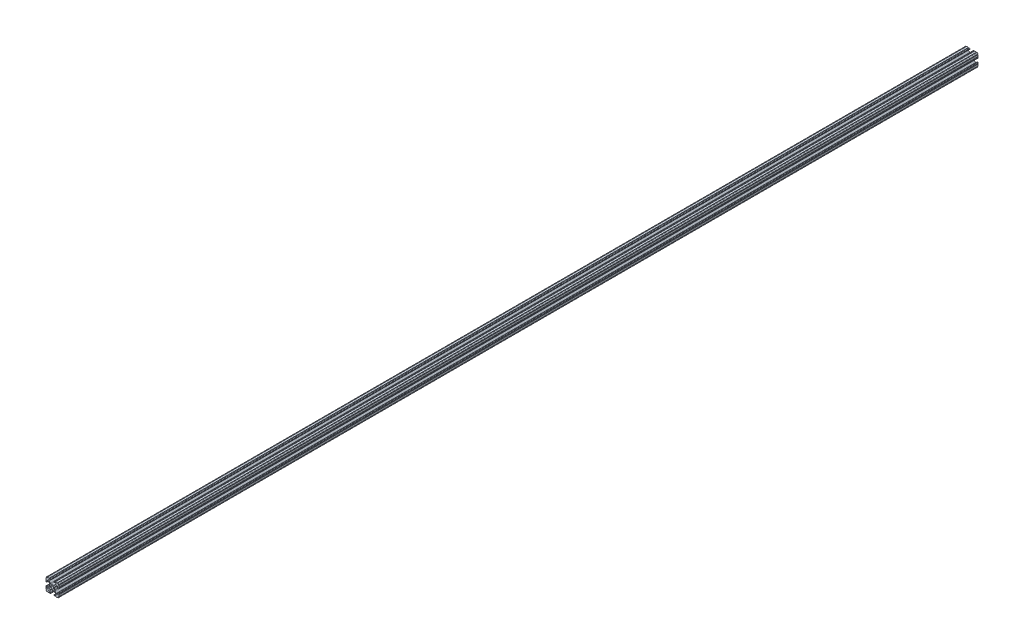
SolidWorks part; units mm, degrees
ref_plane "Front Plane" through (0, 0, 0) normal (0, 0, 1) x (1, 0, 0)
ref_plane "Top Plane" through (0, 0, 0) normal (0, 1, 0) x (1, 0, 0)
ref_plane "Right Plane" through (0, 0, 0) normal (1, 0, 0) x (0, 0, -1)
sketch "Sketch2" plane through (0, 0, 0) normal (0, 0, 1) x (1, 0, 0)
  line L0 (0, 12.7) -> (0, -12.7) construction
  line L1 (-12.7, 0) -> (12.7, 0) construction
  line L2 (3.2512, -12.7) -> (12.7, -12.7)
  line L3 (12.7, -12.7) -> (12.7, -3.2512)
  line L4 (3.2512, -12.7) -> (3.2512, -10.4902)
  line L5 (3.2512, -10.4902) -> (8.9276, -10.4902)
  line L6 (8.9276, -10.4902) -> (3.0856, -4.6482)
  line L7 (0, 0) -> (12.7, -12.7) construction
  line L8 (12.7, -3.2512) -> (10.4902, -3.2512)
  line L9 (10.4902, -3.2512) -> (10.4902, -8.9276)
  line L10 (10.4902, -8.9276) -> (4.6482, -3.0856)
  circle A0 centre (0, 0) radius 2.6035
  arc A1 (6.3485, -10.4902) -> (7.1039, -8.6665) centre (6.3485, -9.4219) ccw construction
  point P8 (0, -4.6482)
  dimension "Center Hole Diameter" = 5.207
  dimension "Rail Height" = 25.4
  dimension "Rail Width" = 25.4
  dimension "T-Slot Width" = 6.5024
  dimension "Slot Inner Width" = 14.8336
  dimension "Thickness" = 2.2098
  dimension "Slot Depth" = 5.842
  dimension "D1" = 2.2098
sketch "Sketch3" plane through (0, 0, 0) normal (1, 0, 0) x (0, 0, -1)
  line L0 (-914.4, -12.7) -> (914.4, -12.7) construction
  line L1 (-889, 0) -> (889, 0) construction
  dimension "Length" = 1828.8
  dimension "D1" = 25.4
sketch "Sketch4" plane through (0, 0, 0) normal (0, 0, 1) x (1, 0, 0)
  line L0 (4.1904, -12.7) -> (10.1173, -12.7)
  line L1 (3.2512, -12.7) -> (12.7, -12.7) construction
  line L2 (3.2512, -12.7) -> (3.2512, -10.4902) construction
  line L3 (3.2512, -10.4902) -> (8.9276, -10.4902) construction
  line L4 (3.2512, -11.4294) -> (3.2512, -11.7608)
  line L5 (4.1904, -10.4902) -> (6.3485, -10.4902)
  line L6 (0, -4.6482) -> (2.164, -4.6482)
  line L7 (8.9276, -10.4902) -> (3.0856, -4.6482) construction
  line L8 (3.7373, -5.2999) -> (7.1039, -8.6665)
  line L9 (12.7, -12.7) -> (12.7, -3.2512) construction
  line L10 (10.4902, -8.9276) -> (4.6482, -3.0856) construction
  line L11 (10.4902, -3.2512) -> (10.4902, -8.9276) construction
  line L12 (10.4902, -6.3485) -> (10.4902, -4.1904)
  line L13 (12.7, -3.2512) -> (10.4902, -3.2512) construction
  line L14 (11.4294, -3.2512) -> (11.7608, -3.2512)
  line L15 (12.7, -4.1904) -> (12.7, -10.1173)
  line L16 (8.6665, -7.1039) -> (5.2999, -3.7373)
  line L17 (4.6482, 0) -> (4.6482, -2.164)
  line L18 (-12.7, 0) -> (12.7, 0) construction
  line L19 (0, -4.6482) -> (0, -2.6035)
  line L20 (0, 12.7) -> (0, -12.7) construction
  line L21 (4.6482, 0) -> (2.6035, 0)
  arc A0 (3.2512, -11.7608) -> (4.1904, -12.7) centre (4.1904, -11.7608) ccw
  arc A2 (3.2512, -11.4294) -> (4.1904, -10.4902) centre (4.1904, -11.4294) cw
  arc A3 (6.3485, -10.4902) -> (7.1039, -8.6665) centre (6.3485, -9.4219) ccw
  arc A4 (2.164, -4.6482) -> (3.7373, -5.2999) centre (2.164, -6.8732) cw
  arc A5 (10.1173, -12.7) -> (12.7, -10.1173) centre (10.1173, -10.1173) ccw
  arc A6 (8.6665, -7.1039) -> (10.4902, -6.3485) centre (9.4219, -6.3485) ccw
  arc A7 (10.4902, -4.1904) -> (11.4294, -3.2512) centre (11.4294, -4.1904) cw
  arc A8 (11.7608, -3.2512) -> (12.7, -4.1904) centre (11.7608, -4.1904) cw
  arc A9 (5.2999, -3.7373) -> (4.6482, -2.164) centre (6.8732, -2.164) cw
  circle A10 centre (0, 0) radius 2.6035 construction
  arc A11 (0, -2.6035) -> (2.6035, 0) centre (0, 0) ccw
  dimension "D1" = 2.5827
  dimension "D2" = 2.225
  dimension "D3" = 0.9392
extrude "Boss-Extrude1" add sketch "Sketch4" along normal mid plane 1828.8
sketch "Sketch5" plane through (0, 0, 0) normal (0, 0, 1) x (1, 0, 0)
  line L0 (3.2512, -12.7) -> (12.7, -12.7) construction
  line L1 (4.1904, -10.4902) -> (6.3485, -10.4902) construction
  line L3 (0, 0) -> (12.7, -12.7) construction
  line L4 (6.3485, -10.4902) -> (6.3485, -12.7) construction
  line L5 (8.9276, -10.4902) -> (3.0856, -4.6482) construction
  circle A0 centre (10.3562, -12.7) radius 0.5524
  circle A1 centre (5.796, -12.7) radius 0.5524
  circle A2 centre (12.7, -10.3562) radius 0.5524
  circle A3 centre (12.7, -5.796) radius 0.5524
  point P10 (5.2694, -10.4902)
  point P12 (9.4219, -6.3485)
  dimension "D1" = 1.1049
extrude "Cut-Extrude1" cut sketch "Sketch5" against normal through all both and the other way through all
mirror "Mirror1" about plane through (0, 0, 0) normal (1, 0, 0) of bodies 137 134
mirror "Mirror2" about plane through (0, 0, 0) normal (0, 1, 0) of bodies 135
equation "\"D1@Boss-Extrude1\"=\"Length@Sketch3\""
equation "\"D1@Sketch2\"=\"Thickness@Sketch2\""
equation "\"D2@Sketch4\"=\"Slot Inner Width@Sketch2\"*0.15"
equation "\"D1@Sketch4\"=\"D3@Sketch4\"*2.75"
equation "\"D3@Sketch4\"=\"Thickness@Sketch2\"*0.425"
equation "\"D1@Sketch5\"=\"Thickness@Sketch2\"*0.5"
